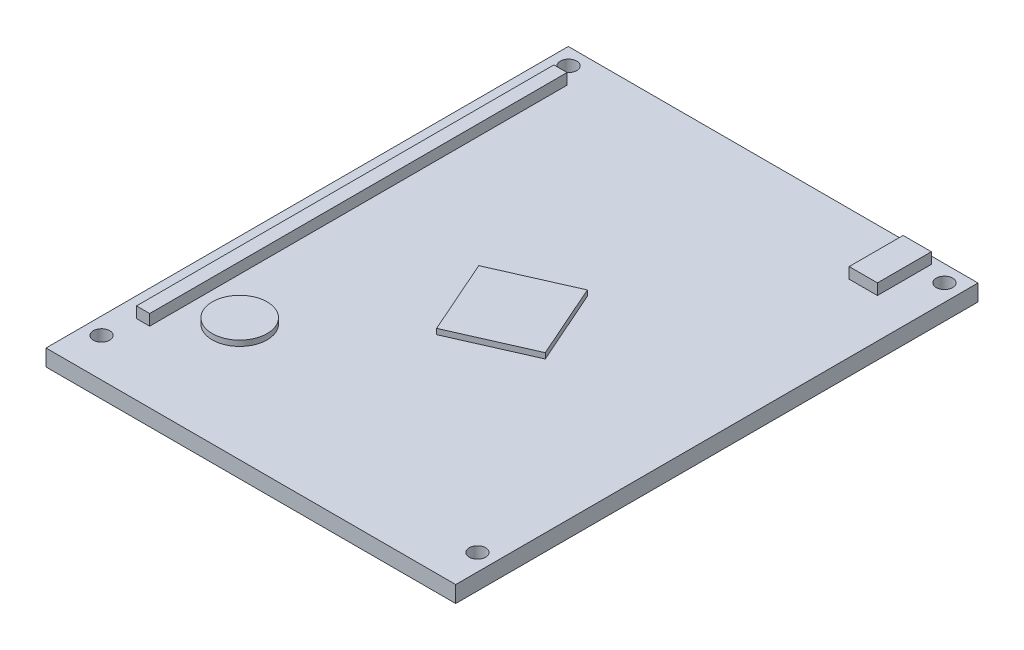
SolidWorks part; units mm, degrees
ref_plane "前视基准面" through (0, 0, 0) normal (0, 0, 1) x (1, 0, 0)
ref_plane "上视基准面" through (0, 0, 0) normal (0, 1, 0) x (1, 0, 0)
ref_plane "右视基准面" through (0, 0, 0) normal (1, 0, 0) x (0, 0, -1)
sketch "草图1" plane through (0, 0, 0) normal (0, 1, 0) x (1, 0, 0)
  line L0 (0, 62.3755) -> (0, -62.9858) construction
  line L1 (-37.3, 47.55) -> (37.3, 47.55)
  line L2 (-37.3, 47.55) -> (-37.3, -47.55)
  line L3 (-37.3, -47.55) -> (37.3, -47.55)
  line L4 (37.3, 47.55) -> (37.3, -47.55)
  line L5 (-37.3, 47.55) -> (37.3, -47.55) construction
  line L6 (-37.3, -47.55) -> (37.3, 47.55) construction
  line L7 (-59.018, 0) -> (57.9719, 0) construction
  circle A0 centre (-34.225, -40.515) radius 1.5
  circle A1 centre (-34.225, 44.515) radius 1.5
  circle A2 centre (34.225, 44.515) radius 1.5
  circle A3 centre (34.225, -40.515) radius 1.5
  point P0 (0, 0)
  dimension "D3" = 3
  dimension "D4" = 3
  dimension "D5" = 3
  dimension "D6" = 3
  dimension "D1" = 95.1
  dimension "D2" = 74.6
  dimension "D7" = 68.45
  dimension "D8" = 68.45
  dimension "D9" = 85.03
  dimension "D10" = 34.225
  dimension "D11" = 34.225
  dimension "D12" = 44.515
  dimension "D13" = 0
  dimension "D14" = 0
  dimension "D15" = 0
extrude "凸台-拉伸1" add sketch "草图1" along normal blind 3
sketch "草图2" plane through (0, 3, 0) normal (0, 1, 0) x (1, 0, 0)
  line L0 (-9.8894, 3.834) -> (-3.834, -9.8894)
  line L1 (-9.8894, 3.834) -> (3.834, 9.8894)
  line L2 (-3.834, -9.8894) -> (9.8894, -3.834)
  line L3 (3.834, 9.8894) -> (9.8894, -3.834)
  line L4 (-9.8894, 3.834) -> (9.8894, -3.834) construction
  line L5 (-3.834, -9.8894) -> (3.834, 9.8894) construction
  point P1 (0, 0)
  dimension "D1" = 15
  dimension "D2" = 15
extrude "凸台-拉伸2" add sketch "草图2" along normal blind 1
sketch "草图3" plane through (0, 3, 0) normal (0, 1, 0) x (1, 0, 0)
  circle A0 centre (-23.4407, -26.1403) radius 5
  dimension "D1" = 10
extrude "凸台-拉伸3" add sketch "草图3" along normal blind 1
sketch "草图4" plane through (0, 3, 0) normal (0, 1, 0) x (1, 0, 0)
  line L0 (-32.5, 43.518) -> (-46.8305, -39.7891) construction
  line L1 (-33.7, 41.3255) -> (-31.3, 41.3255)
  line L2 (-33.7, 41.3255) -> (-33.7, -34.6745)
  line L3 (-33.7, -34.6745) -> (-31.3, -34.6745)
  line L4 (-31.3, 41.3255) -> (-31.3, -34.6745)
  line L5 (-33.7, 41.3255) -> (-31.3, -34.6745) construction
  line L6 (-33.7, -34.6745) -> (-31.3, 41.3255) construction
  line L8 (24.9786, 46.2356) -> (30.1216, 46.2356)
  line L9 (24.9786, 46.2356) -> (24.9786, 36.4153)
  line L10 (24.9786, 36.4153) -> (30.1216, 36.4153)
  line L11 (30.1216, 46.2356) -> (30.1216, 36.4153)
  line L12 (24.9786, 46.2356) -> (30.1216, 36.4153) construction
  line L13 (24.9786, 36.4153) -> (30.1216, 46.2356) construction
  point P0 (-32.5, 3.3255)
  point P8 (27.5501, 41.3255)
  dimension "D1" = 76
  dimension "D2" = 2.4
  dimension "D3" = 32.5
extrude "凸台-拉伸4" add sketch "草图4" along normal blind 2
